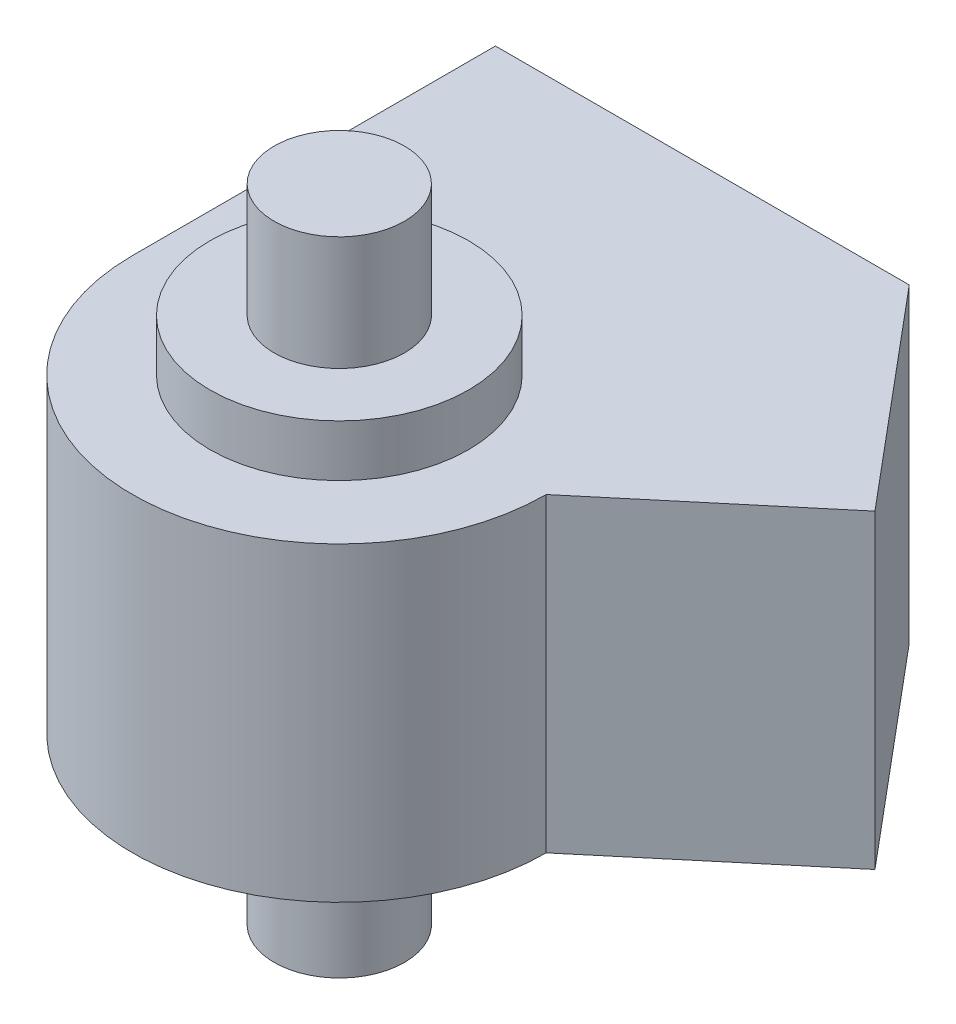
SolidWorks part; units mm, degrees
ref_plane "Front Plane" through (0, 0, 0) normal (0, 0, 1) x (1, 0, 0)
ref_plane "Top Plane" through (0, 0, 0) normal (0, 1, 0) x (1, 0, 0)
ref_plane "Right Plane" through (0, 0, 0) normal (1, 0, 0) x (0, 0, -1)
sketch "Sketch1" plane through (0, 0, 0) normal (0, 0, 1) x (1, 0, 0)
  line L0 (-12.7, -9.525) -> (-12.7, 9.525)
  line L1 (-12.7, 9.525) -> (-7.9375, 9.525)
  line L2 (-7.9375, 9.525) -> (-7.9375, 12.7)
  line L3 (-7.9375, 12.7) -> (-4, 12.7)
  line L4 (-4, 12.7) -> (-4, 19.7)
  line L5 (0, 0) -> (0, 19.7) construction
  line L6 (0, 19.7) -> (-4, 19.7)
  line L7 (0, 0) -> (-12.7, 0) construction
  line L8 (-4, 19.7) -> (4, 19.7) construction
  line L9 (-7.9375, 12.7) -> (7.9375, 12.7) construction
  line L10 (-12.7, 9.525) -> (12.7, 9.525) construction
  line L11 (-12.7, -9.525) -> (-7.9375, -9.525)
  line L12 (-7.9375, -9.525) -> (-7.9375, -12.7)
  line L13 (-7.9375, -12.7) -> (-4, -12.7)
  line L14 (-4, -12.7) -> (-4, -19.7)
  line L15 (-4, -19.7) -> (0, -19.7)
  line L16 (0, -19.7) -> (0, 19.7)
  point P9 (0, 9.525)
  point P12 (0, 19.7)
  point P14 (0, 12.7)
  dimension "D1" = 19.05
  dimension "D2" = 3.175
  dimension "D3" = 7
  dimension "D4" = 8
  dimension "D5" = 15.875
  dimension "D6" = 25.4
  dimension "D7" = 25.4
revolve "Revolve1" add sketch "Sketch1" angle 360 about L5
sketch "Sketch2" plane through (0, 9.525, 0) normal (0, 1, 0) x (1, 0, 0)
  line L0 (12.7, 0) -> (23.6726, 9.2071)
  line L1 (23.6726, 9.2071) -> (12.7, 22.2837)
  line L3 (12.7, 22.2837) -> (-12.7, 22.2837)
  line L4 (-12.7, 22.2837) -> (-12.7, 0)
  line L5 (-12.7, 0) -> (12.7, 0)
  line L6 (12.7, 0) -> (12.7, 22.2837) construction
  circle A0 centre (0, 0) radius 12.7 construction
  dimension "D1" = 50
  dimension "D2" = 25.4
extrude "Boss-Extrude1" add sketch "Sketch2" against normal up to surface (19.05 mm away) up to face at (7.9375, -9.525, 0)
